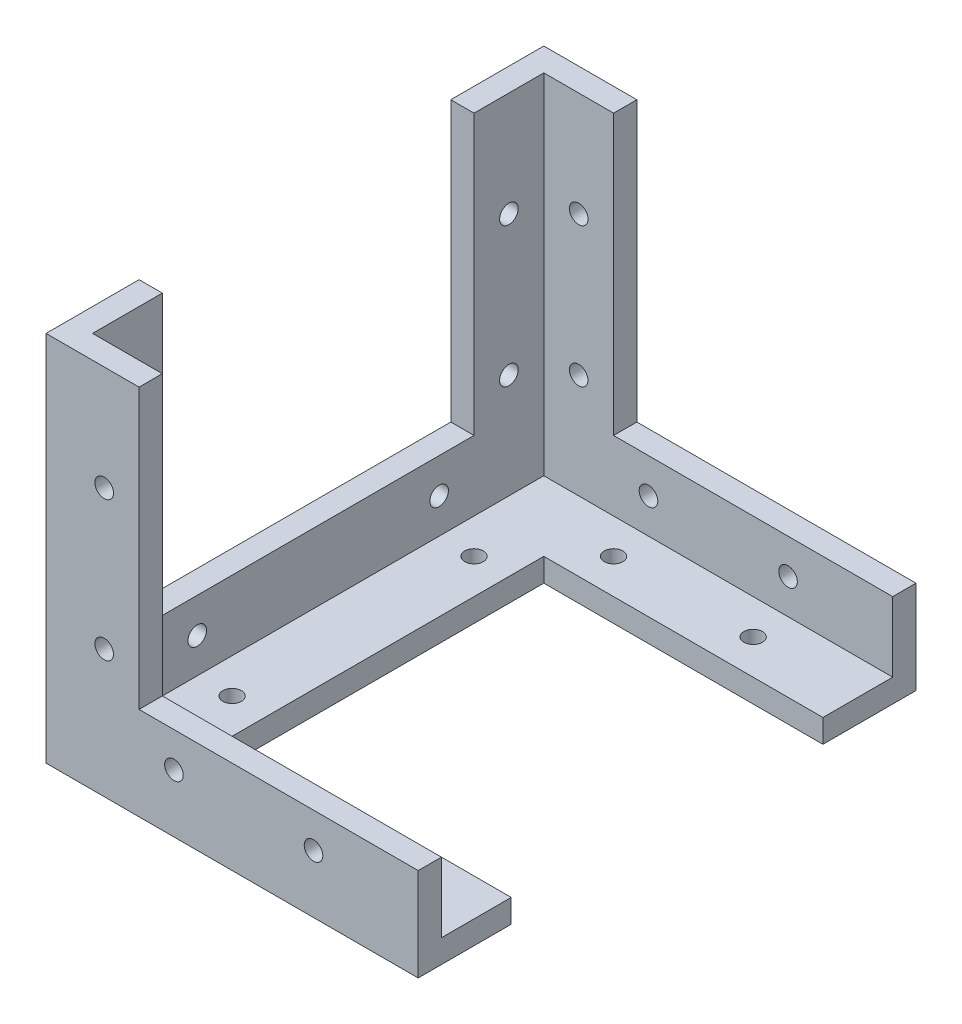
SolidWorks part; units mm, degrees
ref_plane "Front Plane" through (0, 0, 0) normal (0, 0, 1) x (1, 0, 0)
ref_plane "Top Plane" through (0, 0, 0) normal (0, 1, 0) x (1, 0, 0)
ref_plane "Right Plane" through (0, 0, 0) normal (1, 0, 0) x (0, 0, -1)
sketch "Sketch1" plane through (0, 0, 0) normal (0, 1, 0) x (1, 0, 0)
  line L0 (-20, 20) -> (-20, -60)
  line L1 (-20, -60) -> (0, -60)
  line L2 (0, -60) -> (0, 0)
  line L3 (0, 0) -> (60, 0)
  line L4 (60, 0) -> (60, 20)
  line L5 (60, 20) -> (-20, 20)
  dimension "D1" = 20
  dimension "D2" = 80
extrude "Boss-Extrude1" add sketch "Sketch1" against normal blind 5
sketch "Sketch2" plane through (-20, 0, 0) normal (-1, 0, 0) x (0, 0, 1)
  line L0 (-20, -5) -> (60, -5)
  line L1 (60, -5) -> (60, 15)
  line L2 (60, 15) -> (0, 15)
  line L3 (0, 15) -> (0, 75)
  line L4 (0, 75) -> (-20, 75)
  line L5 (-20, 75) -> (-20, -5)
extrude "Boss-Extrude2" add sketch "Sketch2" against normal blind 5
sketch "Sketch3" plane through (0, 0, -20) normal (0, 0, -1) x (-1, 0, 0)
  line L0 (-60, -5) -> (20, -5)
  line L1 (20, -5) -> (20, 75)
  line L2 (20, 75) -> (0, 75)
  line L3 (0, 75) -> (0, 15)
  line L4 (0, 15) -> (-60, 15)
  line L5 (-60, 15) -> (-60, -5)
  point P4 (0, 15.2888)
extrude "Boss-Extrude3" add sketch "Sketch3" against normal blind 5
sketch "Sketch5" plane through (0, 0, 60) normal (0, 0, 1) x (1, 0, 0)
  line L6 (0, 0) -> (-15, 0)
  line L7 (-15, 0) -> (-15, 15)
  line L8 (-15, 15) -> (-20, 15)
  line L9 (-20, 15) -> (-20, -5)
  line L10 (-20, -5) -> (0, -5)
  line L11 (0, -5) -> (0, 0)
  line L12 (0, 0) -> (-15, 0)
  line L13 (-15, 0) -> (-15, 15)
  line L14 (-15, 15) -> (-20, 15)
  line L15 (-20, 15) -> (-20, -5)
  line L16 (-20, -5) -> (0, -5)
  line L17 (0, -5) -> (0, 0)
  dimension "D1" = 0
extrude "hieght extension" add sketch "Sketch5" along normal blind 27
sketch "Sketch6" plane through (0, 0, 87) normal (0, 0, 1) x (1, 0, 0)
  line L0 (-20, 75) -> (-20, -5)
  line L1 (-20, -5) -> (60, -5)
  line L2 (60, -5) -> (60, 15)
  line L3 (60, 15) -> (0, 15)
  line L4 (0, 15) -> (0, 75)
  line L5 (0, 75) -> (-20, 75)
extrude "Boss-Extrude6" add sketch "Sketch6" against normal blind 5
sketch "Sketch7" plane through (-20, 0, 0) normal (-1, 0, 0) x (0, 0, 1)
  line L0 (87, 75) -> (67, 75)
  line L1 (67, 75) -> (67, -5)
  line L2 (-20, -5) -> (87, -5) construction
  line L3 (67, -5) -> (87, -5)
  line L4 (87, -5) -> (87, 75)
  line L5 (0, 75) -> (-20, 75) construction
extrude "Boss-Extrude7" add sketch "Sketch7" against normal blind 5
sketch "Sketch8" plane through (0, -5, 0) normal (0, -1, 0) x (1, 0, 0)
  line L0 (60, 87) -> (60, 67)
  line L1 (60, 67) -> (-20, 67)
  line L2 (-20, -20) -> (-20, 87) construction
  line L3 (-20, 67) -> (-20, 87)
  line L4 (-20, 87) -> (60, 87)
  line L5 (60, 0) -> (60, -20) construction
extrude "Boss-Extrude8" add sketch "Sketch8" against normal blind 5
hole_wizard "Ø4.0mm Dowel Hole1" positions "3DSketch1" profile "Sketch9" hole size "Ø4.0" standard "ANSI Metric"
sketch3d "3DSketch1"
  line L0 (-15, 0, 82) -> (-15, 75, 82) construction
  line L1 (-15, 0, 82) -> (60, 0, 82) construction
  line L2 (-15, 0, -15) -> (-15, 0, 82) construction
  line L3 (-15, 75, -15) -> (-15, 0, -15) construction
  line L4 (60, 0, -15) -> (-15, 0, -15) construction
  line L5 (-15, 22.5, -15) -> (-15, 52.5, -15) construction
  line L10 (7.5, 0, -15) -> (37.5, 0, -15) construction
  line L12 (-15, 0, 7.5) -> (-15, 0, 59.5) construction
  line L13 (-15, 75, 0) -> (-15, 75, -15) construction
  line L14 (-15, 75, -15) -> (0, 75, -15) construction
  line L15 (-15, 75, 82) -> (-15, 75, 67) construction
  line L16 (0, 75, 82) -> (-15, 75, 82) construction
  line L17 (60, 0, 82) -> (60, 15, 82) construction
  line L18 (60, 0, 67) -> (60, 0, 82) construction
  line L19 (60, 0, 0) -> (60, 0, -15) construction
  line L20 (60, 15, -15) -> (60, 0, -15) construction
  line L21 (-15, 15, 0) -> (-15, 0, 0) construction
  line L22 (-15, 0, 0) -> (0, 0, 0) construction
  line L24 (7.5, 0, 74.5) -> (-7.5, 0, 59.5) construction
  line L26 (0, 0, 67) -> (0, 0, 0) construction
  point P0 (-15, 52.5, 74.5)
  point P2 (-15, 22.5, 74.5)
  point P4 (-15, 7.5, 7.5)
  point P6 (-15, 7.5, 59.5)
  point P8 (7.5, 0, 74.5)
  point P10 (37.5, 0, 74.5)
  point P12 (-7.5, 0, 7.5)
  point P14 (-7.5, 0, 59.5)
  point P16 (7.5, 0, -7.5)
  point P18 (37.5, 0, -7.5)
  point P20 (-15, 22.5, -7.5)
  point P22 (-15, 52.5, -7.5)
  point P24 (-7.5, 52.5, 82)
  point P26 (-7.5, 22.5, 82)
  point P28 (7.5, 7.5, 82)
  point P30 (37.5, 7.5, 82)
  point P32 (37.5, 7.5, -15)
  point P34 (7.5, 7.5, -15)
  point P36 (-7.5, 22.5, -15)
  point P38 (-7.5, 52.5, -15)
  point P53 (-15, 52.5, 82)
  point P57 (-15, 22.5, 82)
  point P59 (7.5, 0, 82)
  point P63 (37.5, 0, 82)
  point P65 (-15, 0, 7.5)
  point P69 (-15, 0, 59.5)
  point P71 (-15, 22.5, -15)
  point P75 (-15, 52.5, -15)
  point P77 (7.5, 0, -15)
  point P81 (37.5, 0, -15)
  point P132 (-15, 37.5, -15)
  point P136 (-15, 37.5, -15)
  point P140 (22.5, 0, -15)
  point P146 (22.5, 0, -15)
  point P151 (-15, 0, 33.5)
  point P154 (-15, 0, 33.5)
  point P155 (-15, 75, -7.5)
  point P159 (-7.5, 75, -15)
  point P163 (-15, 75, 74.5)
  point P167 (-7.5, 75, 82)
  point P171 (60, 7.5, 82)
  point P175 (60, 0, 74.5)
  point P179 (60, 0, -7.5)
  point P183 (60, 7.5, -15)
  point P202 (-7.5, 0, 0)
  point P204 (-15, 7.5, 0)
  dimension "D1" = 30
  dimension "D2" = 45
sketch "Sketch9" plane through (-15, 52.5, 74.5) normal (0, 1, 0) x (0, 0, -1)
  line L0 (0, 0) -> (0, 5)
  line L1 (0, 5) -> (2, 5)
  line L2 (2, 5) -> (2, 0)
  line L5 (2, 0) -> (0, 0)
  line L11 (0, -6.35) -> (0, 107.95) construction
  dimension "Thru Hole Dia." = 4
  dimension "Thru Hole Depth" = 5
